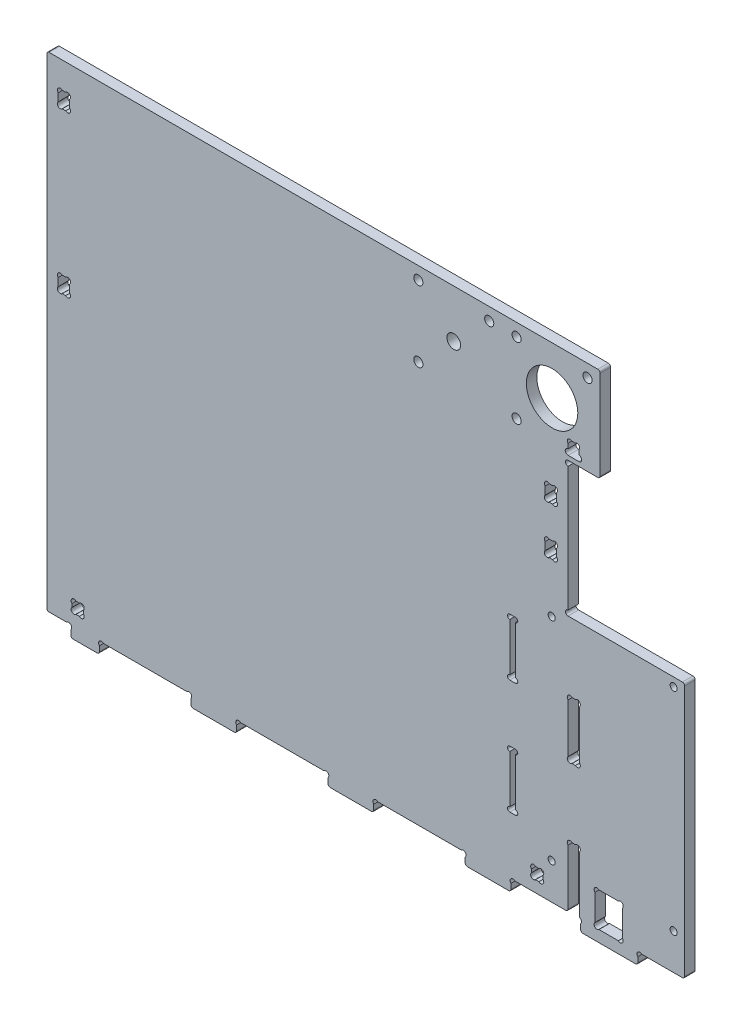
SolidWorks part; units mm, degrees
ref_plane "Front Plane" through (0, 0, 0) normal (0, 0, 1) x (1, 0, 0)
ref_plane "Top Plane" through (0, 0, 0) normal (0, 1, 0) x (1, 0, 0)
ref_plane "Right Plane" through (0, 0, 0) normal (1, 0, 0) x (0, 0, -1)
sketch "Sketch1" plane through (0, 0, 0) normal (0, 0, 1) x (1, 0, 0)
  line L1 (0, 0) -> (10.5, 0)
  line L2 (0, 0) -> (0, 212)
  line L3 (183.4453, 212) -> (242, 212)
  line L4 (242, 172.67) -> (242, 212)
  line L6 (23, 0) -> (63, 0)
  line L7 (212, 172.67) -> (228, 172.67) construction
  line L8 (228, 0) -> (228, 50)
  line L9 (0, 212) -> (161.9969, 212)
  line L12 (161.9969, 212) -> (183.4453, 212)
  line L13 (228, 75) -> (228, 170.97)
  line L16 (228, 75) -> (279, 75) construction
  line L17 (23, 0) -> (23, -5)
  line L18 (228, 50) -> (279, 50) construction
  line L19 (279, 75) -> (279, 50) construction
  line L20 (23, -5) -> (10.5, -5)
  line L21 (10.5, 0) -> (10.5, -5)
  line L22 (212, 10) -> (217, 10)
  line L23 (212, 10) -> (212, 5)
  line L24 (212, 5) -> (217, 5)
  line L25 (217, 10) -> (217, 5)
  line L26 (11, 10) -> (16, 10)
  line L27 (11, 10) -> (11, 5)
  line L28 (11, 5) -> (16, 5)
  line L29 (16, 10) -> (16, 5)
  line L32 (228, 170.97) -> (228, 172.67) construction
  line L33 (228, 75) -> (228, 50)
  line L34 (83, 0) -> (123, 0)
  line L35 (203, 0) -> (228, 0)
  line L37 (220, 168.97) -> (220, 172.67) construction
  line L38 (63, 0) -> (63, -5)
  line L39 (63, -5) -> (83, -5)
  line L40 (83, 0) -> (83, -5)
  line L41 (228, 172.67) -> (242, 172.67) construction
  line L42 (183, 0) -> (183, -5)
  line L43 (183, -5) -> (203, -5)
  line L44 (203, 0) -> (203, -5)
  line L45 (223, 137) -> (218, 137)
  line L46 (143, 0) -> (183, 0)
  line L48 (218, 137) -> (218, 130)
  line L49 (223, 137) -> (223, 130)
  line L50 (123, 0) -> (123, -5)
  line L51 (123, -5) -> (143, -5)
  line L52 (143, 0) -> (143, -5)
  line L53 (223, 130) -> (218, 130)
  line L54 (218, 151) -> (223, 151)
  line L55 (218, 151) -> (218, 158)
  line L56 (218, 158) -> (223, 158)
  line L57 (223, 151) -> (223, 158)
  line L58 (228, 170.97) -> (242, 170.97)
  line L64 (212, 172.67) -> (212, 170.97) construction
  line L67 (212, 170.97) -> (216, 170.97) construction
  line L70 (216, 170.97) -> (216, 168.97) construction
  line L71 (216, 168.97) -> (224, 168.97) construction
  line L72 (224, 170.97) -> (224, 168.97) construction
  line L73 (5, 200.5) -> (10, 200.5)
  line L76 (5, 200.5) -> (5, 193.5)
  line L77 (5, 193.5) -> (10, 193.5)
  line L79 (10, 200.5) -> (10, 193.5)
  line L80 (5, 130.5) -> (10, 130.5)
  line L81 (5, 130.5) -> (5, 123.5)
  line L83 (228, 179.07) -> (232.7, 179.07)
  line L84 (5, 123.5) -> (10, 123.5)
  line L85 (10, 130.5) -> (10, 123.5)
  line L86 (5, 197) -> (10, 197) construction
  line L87 (5, 127) -> (10, 127) construction
  line L91 (224, 170.97) -> (228, 170.97) construction
  line L92 (228, 179.07) -> (228, 172.87)
  line L93 (228, 172.87) -> (232.7, 172.87)
  line L94 (232.7, 179.07) -> (232.7, 172.87)
  line L95 (242, 170.97) -> (242, 172.67)
  point P29 (223, 144)
  point P65 (133, 0)
  point P72 (133, -5)
  dimension "D11" = 5
  dimension "D13" = 100
  dimension "D20" = 14
  dimension "D22" = 1.7
  dimension "D10" = 5
  dimension "D15" = 133
  dimension "D27" = 8
  dimension "D52" = 5
  dimension "D6" = 1.9
  dimension "D3" = 228
  dimension "D7" = 61
  dimension "D8" = 20
  dimension "D9" = 5
  dimension "D12" = 16
  dimension "D14" = 10
  dimension "D16" = 75
  dimension "D17" = 7
  dimension "D18" = 11
  dimension "D21" = 9.3
  dimension "D25" = 242
  dimension "D26" = 39.33
  dimension "D29" = 16
  dimension "D30" = 7
  dimension "D31" = 25
  dimension "D32" = 2
  dimension "D33" = 4.7
  dimension "D34" = 12.5
  dimension "D35" = 279
  dimension "D36" = 25
  dimension "D37" = 40
  dimension "D38" = 10.5
  dimension "D39" = 5
  dimension "D40" = 5
  dimension "D41" = 5
  dimension "D42" = 5
  dimension "D43" = 6.2
  dimension "D44" = 5
  dimension "D45" = 7
  dimension "D46" = 70
  dimension "D47" = 212
  dimension "D48" = 14
  dimension "D49" = 50
  dimension "D50" = 11.5
  dimension "D51" = 5
extrude "Boss-Extrude1" add sketch "Sketch1" along normal blind 4.6
sketch "Sketch2" plane through (0, 0, 4.6) normal (0, 0, 1) x (1, 0, 0)
  line L0 (242, 212) -> (0, 212) construction
  line L1 (205.5, 175.5) -> (236.5, 175.5) construction
  line L2 (205.5, 175.5) -> (205.5, 206.5) construction
  line L3 (205.5, 206.5) -> (236.5, 206.5) construction
  line L4 (236.5, 175.5) -> (236.5, 206.5) construction
  line L5 (205.5, 175.5) -> (236.5, 206.5) construction
  line L6 (205.5, 206.5) -> (236.5, 175.5) construction
  line L7 (193.5, 175.5) -> (193.5, 206.5) construction
  line L8 (0, 212) -> (0, 0) construction
  line L9 (162.5, 206.5) -> (193.5, 206.5) construction
  line L10 (162.5, 175.5) -> (193.5, 175.5) construction
  line L12 (162.5, 175.5) -> (162.5, 206.5) construction
  line L13 (162.5, 206.5) -> (193.5, 175.5) construction
  line L14 (162.5, 175.5) -> (193.5, 206.5) construction
  circle A0 centre (221, 191) radius 11.25
  circle A1 centre (205.5, 206.5) radius 2
  circle A2 centre (205.5, 175.5) radius 2
  circle A3 centre (236.5, 175.5) radius 2 construction
  circle A4 centre (236.5, 206.5) radius 2
  circle A5 centre (162.5, 206.5) radius 2
  circle A6 centre (162.5, 175.5) radius 2
  circle A7 centre (193.5, 206.5) radius 2
  circle A8 centre (193.5, 175.5) radius 2 construction
  circle A9 centre (178, 191) radius 3
  dimension "D1" = 4
  dimension "D2" = 22.5
  dimension "D6" = 12
  dimension "D3" = 21
  dimension "D7" = 4
  dimension "D8" = 6
  dimension "D4" = 221
  dimension "D5" = 31
extrude "Cut-Extrude1" cut sketch "Sketch2" against normal through all
sketch "Sketch9" plane through (0, 0, 4.6) normal (0, 0, 1) x (1, 0, 0)
  line L0 (228, 0) -> (228, 170.97) construction
  line L1 (228, 112) -> (233, 112)
  line L2 (228, 112) -> (228, 82)
  line L3 (228, 82) -> (233, 82)
  line L4 (233, 112) -> (233, 82)
  line L5 (242, 212) -> (0, 212) construction
  line L6 (228, 0) -> (228, 170.97) construction
  line L7 (228, 57) -> (233, 57)
  line L8 (228, 57) -> (228, 27)
  line L9 (228, 27) -> (233, 27)
  line L10 (233, 57) -> (233, 27)
  point P6 (228, 97)
  dimension "D1" = 5
  dimension "D2" = 30
  dimension "D3" = 115
  dimension "D4" = 25
extrude "Boss-Extrude2" add sketch "Sketch9" against normal up to surface (4.6 mm away) up to face at (181, 191, 0)
sketch "Sketch13" plane through (0, 0, 4.6) normal (0, 0, 1) x (1, 0, 0)
  line L0 (228, 112) -> (228, 170.97) construction
  line L1 (233, 112) -> (279, 112)
  line L2 (233, 112) -> (233, 0)
  line L3 (233, 0) -> (279, 0)
  line L4 (279, 112) -> (279, 0)
  line L5 (203, 0) -> (228, 0) construction
  dimension "D1" = 51
extrude "Boss-Extrude4" add sketch "Sketch13" against normal up to surface (4.6 mm away) up to face at (181, 191, 0)
sketch "Sketch14" plane through (0, 0, 4.6) normal (0, 0, 1) x (1, 0, 0)
  line L0 (233, 0) -> (279, 0) construction
  line L1 (233.5, 0) -> (258.5, 0)
  line L2 (233.5, 0) -> (233.5, -5)
  line L3 (233.5, -5) -> (258.5, -5)
  line L4 (258.5, 0) -> (258.5, -5)
  line L5 (183, -5) -> (203, -5) construction
  line L7 (279, 0) -> (279, 112) construction
  dimension "D1" = 25
  dimension "D2" = 20.5
extrude "Boss-Extrude5" add sketch "Sketch14" against normal up to surface (4.6 mm away) up to face at (145.8214, 35.855, 0)
sketch "Sketch17" plane through (0, 0, 4.6) normal (0, 0, 1) x (1, 0, 0)
  line L3 (279, 0) -> (279, 112) construction
  line L4 (203, 0) -> (228, 0) construction
  line L5 (202.5, 100) -> (205, 100)
  line L6 (202.5, 100) -> (202.5, 75)
  line L7 (202.5, 75) -> (205, 75)
  line L8 (205, 100) -> (205, 75)
  line L9 (202.5, 50) -> (205, 50)
  line L10 (202.5, 50) -> (202.5, 25)
  line L11 (202.5, 25) -> (205, 25)
  line L12 (205, 50) -> (205, 25)
  dimension "D1" = 74
  dimension "D2" = 25
  dimension "D3" = 25
  dimension "D4" = 2.5
  dimension "D6" = 25
  dimension "D7" = 25
extrude "Cut-Extrude17" cut sketch "Sketch17" against normal through all
sketch "Sketch19" plane through (0, 0, 4.6) normal (0, 0, 1) x (1, 0, 0)
  line L1 (239.75, 0) -> (251.75, 0)
  line L2 (239.75, 0) -> (239.75, 15)
  line L3 (239.75, 15) -> (251.75, 15)
  line L4 (251.75, 0) -> (251.75, 15)
  line L5 (279, 0) -> (279, 112) construction
  dimension "D1" = 15
  dimension "D2" = 12
  dimension "D3" = 39.25
extrude "Cut-Extrude20" cut sketch "Sketch19" against normal through all
sketch "Sketch16" plane through (0, 0, 4.6) normal (0, 0, 1) x (1, 0, 0)
  line L0 (7.5, 200.5) -> (7.5, 197) construction
  line L1 (220, 168.97) -> (220, 172.67) construction
  line L2 (7.5, 197) -> (5, 197) construction
  line L3 (212, 170.97) -> (212, 172.67) construction
  line L4 (245.75, 15) -> (245.75, 0) construction
  line L5 (5.8839, 200.5) -> (5.8839, 199.6161) construction
  line L6 (5.8839, 199.6161) -> (5, 199.6161) construction
  line L7 (251.6034, 7.5) -> (239.7841, 7.5) construction
  line L8 (228, 112) -> (228, 170.97) construction
  line L9 (239.75, 15) -> (251.75, 15) construction
  line L10 (279, 112) -> (228, 112) construction
  line L11 (233.5, 0) -> (258.5, 0) construction
  line L12 (224, 168.97) -> (224, 170.97) construction
  line L13 (11.8839, 10) -> (11.8839, 9.1161) construction
  line L14 (239.75, 0) -> (239.75, 15) construction
  line L15 (16, 10) -> (11, 10) construction
  line L16 (16.9424, 162) -> (2.7197, 162) construction
  line L17 (212, 172.67) -> (212, 170.97) construction
  line L20 (11.8839, 9.1161) -> (11, 9.1161) construction
  line L21 (11, 10) -> (11, 5) construction
  line L22 (13.5, 10) -> (13.5, 7.5) construction
  line L23 (13.5, 7.5) -> (11, 7.5) construction
  line L24 (212, 170.97) -> (216, 170.97) construction
  line L25 (5, 200.5) -> (5, 193.5) construction
  line L26 (228, 170.97) -> (242, 170.97) construction
  line L27 (232.7, 174.12) -> (228, 174.12) construction
  line L29 (216, 168.97) -> (224, 168.97) construction
  line L32 (220.5, 158) -> (220.5, 154.5) construction
  line L33 (223, 158) -> (218, 158) construction
  line L34 (220.5, 154.5) -> (218, 154.5) construction
  line L35 (218, 158) -> (218, 151) construction
  line L36 (218.8839, 158) -> (218.8839, 157.1161) construction
  line L37 (218.8839, 157.1161) -> (218, 157.1161) construction
  line L38 (216.4656, 144) -> (218.25, 144) construction
  line L39 (218, 151) -> (223, 151) construction
  line L40 (223, 137) -> (218, 137) construction
  line L42 (246, -5) -> (246, 3.5516) construction
  line L44 (233.5, -5) -> (258.5, -5) construction
  line L45 (233.5, 0) -> (233.5, -5) construction
  line L46 (16, 5) -> (16, 10) construction
  line L48 (114, 17.8957) -> (114, 41.2157) construction
  line L49 (212, 10) -> (212, 5) construction
  line L50 (10.5, -5) -> (23, -5) construction
  line L51 (16.75, -5) -> (16.75, -1.5467) construction
  line L52 (203, -5) -> (203, 0) construction
  line L53 (9.6161, 0) -> (9.6161, -0.8839) construction
  line L54 (0, 0) -> (10.5, 0) construction
  line L55 (43, 0) -> (43, 10) construction
  line L56 (23, 0) -> (63, 0) construction
  line L57 (9.6161, -0.8839) -> (10.5, -0.8839) construction
  line L58 (10.5, 0) -> (10.5, -5) construction
  line L59 (212, 172.67) -> (228, 172.67) construction
  line L60 (73, -5) -> (73, 10.7685) construction
  line L61 (63, -5) -> (83, -5) construction
  line L63 (83, 0) -> (123, 0) construction
  line L64 (103, 0) -> (103, 7.5) construction
  line L65 (224, 170.97) -> (228, 170.97) construction
  line L66 (123, -5) -> (143, -5) construction
  line L67 (133, -5) -> (133, 1.8443) construction
  line L68 (228.8839, 27) -> (228.8839, 26.1161) construction
  line L69 (143, 0) -> (183, 0) construction
  line L70 (163, 0) -> (163, 10) construction
  line L71 (228, 27) -> (233, 27) construction
  line L72 (183, -5) -> (203, -5) construction
  line L73 (193, -5) -> (193, 5) construction
  line L74 (228.8839, 26.1161) -> (228, 26.1161) construction
  line L75 (228, 0) -> (228, 27) construction
  line L76 (230.5, 27) -> (230.5, 25.1107) construction
  line L77 (226.6019, 42) -> (234.5105, 42) construction
  line L78 (233, 57) -> (228, 57) construction
  line L79 (233, 69.5) -> (230.8765, 69.5) construction
  line L80 (233, 82) -> (233, 57) construction
  line L81 (214.2105, 173.47) -> (216, 173.47) construction
  line L82 (10, 200.5) -> (5, 200.5) construction
  line L84 (214.5, 170.97) -> (216, 170.97) construction
  line L85 (224, 173.47) -> (228, 173.47) construction
  line L86 (216, 168.97) -> (216, 170.97) construction
  line L87 (218.25, -8.543) -> (218.25, -2.5) construction
  line L88 (10, 130.5) -> (5, 130.5) construction
  line L89 (5, 193.5) -> (10, 193.5) construction
  line L90 (205, 50) -> (202.5, 50) construction
  line L91 (216, 170.97) -> (216, 168.97) construction
  line L92 (202.5, 25) -> (205, 25) construction
  line L93 (232.7, 172.87) -> (232.7, 179.07) construction
  line L94 (217.1662, 172.67) -> (222.8338, 172.67) construction
  line L95 (232.7, 172.87) -> (228, 172.87)
  line L96 (205, 50) -> (202.5, 50) construction
  line L97 (205, 25) -> (205, 50) construction
  line L98 (232.7, 175.37) -> (228, 175.37)
  line L99 (218.5, 168.97) -> (221.5, 168.97) construction
  line L101 (202.5, 75) -> (205, 75) construction
  line L102 (202.5, 50) -> (202.5, 25) construction
  line L103 (202.5, 37.5) -> (206, 37.5) construction
  line L105 (201.0939, 62.5) -> (206, 62.5) construction
  line L107 (205, 75) -> (205, 100) construction
  line L108 (205, 87.5) -> (201.0939, 87.5) construction
  line L109 (202.5, 26) -> (205, 26) construction
  line L111 (202.5, 25) -> (205, 25)
  line L114 (202.5, 27) -> (205, 27)
  line L115 (202.5, 49) -> (205, 49) construction
  line L116 (202.5, 50) -> (205, 50)
  line L117 (202.5, 48) -> (205, 48)
  line L118 (202.5, 76) -> (205, 76) construction
  line L119 (202.5, 75) -> (205, 75)
  line L120 (202.5, 77) -> (205, 77)
  line L121 (202.5, 99) -> (205, 99) construction
  line L122 (202.5, 100) -> (205, 100)
  line L123 (202.5, 98) -> (205, 98)
  line L139 (232.7, 178.2745) -> (231.9045, 178.2745) construction
  line L140 (228, 179.07) -> (228, 172.87) construction
  line L141 (231.9045, 178.2745) -> (231.9045, 179.07) construction
  line L142 (232.7, 179.07) -> (228, 179.07) construction
  line L144 (228, 172.87) -> (232.7, 172.87) construction
  line L145 (230.35, 179.07) -> (230.35, 177.6555) construction
  circle A0 centre (5.8839, 199.6161) radius 1.25
  circle A1 centre (9.1161, 199.6161) radius 1.25
  circle A2 centre (9.1161, 194.3839) radius 1.25
  circle A3 centre (5.8839, 194.3839) radius 1.25
  circle A4 centre (9.1161, 129.6161) radius 1.25
  circle A5 centre (5.8839, 129.6161) radius 1.25
  circle A6 centre (9.1161, 124.3839) radius 1.25
  circle A7 centre (5.8839, 124.3839) radius 1.25
  circle A8 centre (228, 169.845) radius 1.125
  circle A9 centre (228, 113.125) radius 1.125
  circle A10 centre (218.8839, 157.1161) radius 1.25
  circle A11 centre (222.1161, 157.1161) radius 1.25
  circle A12 centre (222.1161, 151.8839) radius 1.25
  circle A13 centre (218.8839, 151.8839) radius 1.25
  circle A14 centre (11.8839, 9.1161) radius 1.25
  circle A15 centre (11.8839, 5.8839) radius 1.25
  circle A16 centre (15.1161, 9.1161) radius 1.25
  circle A17 centre (15.1161, 5.8839) radius 1.25
  circle A18 centre (212.8839, 5.8839) radius 1.25
  circle A19 centre (212.8839, 9.1161) radius 1.25
  circle A20 centre (216.1161, 5.8839) radius 1.25
  circle A21 centre (216.1161, 9.1161) radius 1.25
  circle A22 centre (240.63, 14.12) radius 1.25
  circle A23 centre (240.63, 0.88) radius 1.25
  circle A24 centre (250.87, 0.88) radius 1.25
  circle A25 centre (250.87, 14.12) radius 1.25
  circle A26 centre (9.6161, -0.8839) radius 1.25
  circle A27 centre (23.8839, -0.8839) radius 1.25
  circle A28 centre (62.1161, -0.8839) radius 1.25
  circle A29 centre (83.8839, -0.8839) radius 1.25
  arc A31 (212, 170.97) -> (214.5, 170.97) centre (213.25, 170.97) ccw construction
  circle A32 centre (222.1161, 136.1161) radius 1.25
  circle A33 centre (218.8839, 136.1161) radius 1.25
  circle A34 centre (222.1161, 130.8839) radius 1.25
  circle A35 centre (218.8839, 130.8839) radius 1.25
  circle A36 centre (122.1161, -0.8839) radius 1.25
  circle A37 centre (143.8839, -0.8839) radius 1.25
  circle A38 centre (182.1161, -0.8839) radius 1.25
  circle A39 centre (203.8839, -0.8839) radius 1.25
  circle A40 centre (232.6161, -0.8839) radius 1.25
  circle A41 centre (259.3839, -0.8839) radius 1.25
  arc A42 (214.2105, 173.47) -> (212, 172.67) centre (213.25, 172.67) ccw construction
  arc A43 (222.8338, 172.67) -> (224, 173.47) centre (224, 172.22) cw construction
  arc A44 (224, 168.97) -> (221.5, 168.97) centre (222.75, 168.97) cw construction
  arc A45 (216, 168.97) -> (218.5, 168.97) centre (217.25, 168.97) ccw construction
  circle A46 centre (228.8839, 26.1161) radius 1.25
  circle A47 centre (232.1161, 26.1161) radius 1.25
  circle A48 centre (232.1161, 57.8839) radius 1.25
  circle A49 centre (228.8839, 57.8839) radius 1.25
  circle A50 centre (228.8839, 81.1161) radius 1.25
  circle A51 centre (232.1161, 81.1161) radius 1.25
  arc A52 (228, 170.97) -> (228, 173.47) centre (228, 172.22) ccw construction
  arc A53 (232.7, 172.87) -> (232.7, 175.37) centre (232.7, 174.12) ccw
  arc A55 (228, 175.37) -> (228, 172.87) centre (228, 174.12) ccw
  arc A56 (202.5, 25) -> (202.5, 27) centre (202.5, 26) cw
  arc A57 (205, 27) -> (205, 25) centre (205, 26) cw
  arc A58 (217.1662, 172.67) -> (216, 173.47) centre (216, 172.22) ccw construction
  arc A59 (202.5, 50) -> (202.5, 48) centre (202.5, 49) ccw
  arc A60 (205, 48) -> (205, 50) centre (205, 49) ccw
  arc A61 (202.5, 75) -> (202.5, 77) centre (202.5, 76) cw
  arc A62 (205, 77) -> (205, 75) centre (205, 76) cw
  arc A63 (202.5, 100) -> (202.5, 98) centre (202.5, 99) ccw
  arc A64 (205, 98) -> (205, 100) centre (205, 99) ccw
  circle A73 centre (231.9045, 178.2745) radius 1.125
  circle A74 centre (228.7955, 178.2745) radius 1.125
  point P151 (213.25, 171.82)
  point P210 (214.625, 172.22)
  point P217 (217.25, 170.195)
  point P273 (222.75, 170.195)
  point P276 (225.375, 172.22)
  point P277 (226.75, 171.82)
  point P296 (230.35, 174.12)
  point P323 (203.75, 26)
  point P330 (203.75, 49)
  point P337 (203.75, 76)
  point P344 (203.75, 99)
  dimension "D2" = 2.5
  dimension "D4" = 2.5
  dimension "D3" = 2.5
  dimension "D5" = 2.5
  dimension "D6" = 0.88
  dimension "D7" = 1.25
  dimension "D8" = 4
  dimension "D9" = 5.7895
  dimension "D10" = 2.5
  dimension "D14" = 1
  dimension "D13" = 0.88
  dimension "D15" = 1.25
  dimension "D16" = 2.25
  dimension "D17" = 2.5
  dimension "D18" = 7.5
  dimension "D19" = 7.5
  dimension "D11" = 1.5
  dimension "D12" = 5.5
extrude "Cut-Extrude13" cut sketch "Sketch16" against normal through all
sketch "Sketch18" plane through (0, 0, 4.6) normal (0, 0, 1) x (1, 0, 0)
  circle A0 centre (274.17, 108.228) radius 1.55
  circle A1 centre (220.83, 108.228) radius 1.55
  circle A2 centre (274.17, 15.772) radius 1.55
  circle A3 centre (220.83, 15.772) radius 1.55
  circle A4 centre (274.17, 108.228) radius 1.5 construction
  circle A5 centre (220.83, 108.228) radius 1.5 construction
  circle A6 centre (274.17, 15.772) radius 1.5 construction
  circle A7 centre (220.83, 15.772) radius 1.5 construction
  dimension "D1" = 3.1
extrude "Cut-Extrude18" cut sketch "Sketch18" against normal through all
fillet "Fillet1" radius 1 17 edges at (279, 0, 2.3) (279, 112, 2.3) (258.5, -5, 2.3) (233.5, -5, 2.3) (0, 212, 2.3) (242, 212, 2.3) (242, 170.97, 2.3) (228, 0, 2.3) (203, -5, 2.3) (183, -5, 2.3) (143, -5, 2.3) (123, -5, 2.3) (83, -5, 2.3) (63, -5, 2.3) (23, -5, 2.3) (10.5, -5, 2.3) (0, 0, 2.3)
